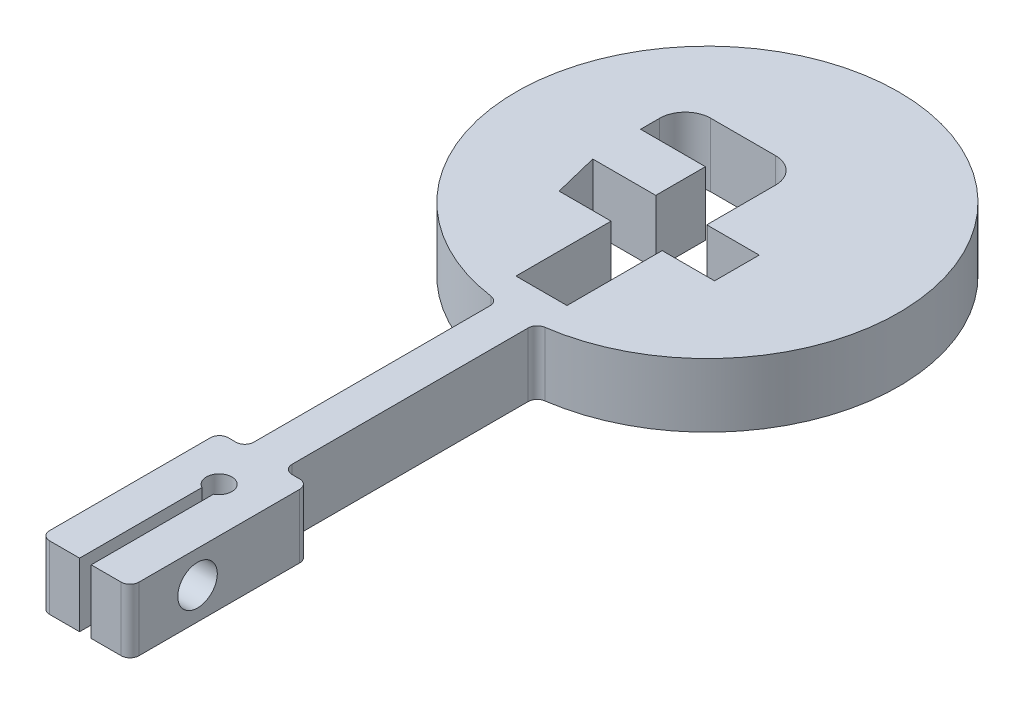
SolidWorks part; units mm, degrees
ref_plane "Front Plane" through (0, 0, 0) normal (0, 0, 1) x (1, 0, 0)
ref_plane "Top Plane" through (0, 0, 0) normal (0, 1, 0) x (1, 0, 0)
ref_plane "Right Plane" through (0, 0, 0) normal (1, 0, 0) x (0, 0, -1)
sketch "Sketch3" plane through (0, 0, 0) normal (0, 1, 0) x (1, 0, 0)
  line L0 (0.4546, -7) -> (0.4546, 2.8262)
  line L5 (-3.5, -7) -> (3.5, -7)
  line L6 (-3.5, -7) -> (-3.5, 7)
  line L7 (-3.5, 7) -> (3.5, 7)
  line L8 (3.5, -7) -> (3.5, 7)
  line L9 (-3.5, -7) -> (3.5, 7) construction
  line L10 (-3.5, 7) -> (3.5, -7) construction
  line L11 (0, -7) -> (-0.4546, -7)
  line L13 (0.4546, 2.8262) -> (-0.4546, 2.8262)
  line L14 (-0.4546, -7) -> (-0.4546, 2.8262)
  line L16 (-1.5, 7) -> (1.5, 7)
  line L17 (-1.5, 7) -> (-1.5, 27)
  line L19 (1.5, 7) -> (1.5, 27)
  line L20 (-1.5, 7) -> (1.5, 27) construction
  line L21 (-1.5, 27) -> (1.5, 7) construction
  line L24 (-1.5, 47.6013) -> (2.5, 47.6013)
  line L34 (0, 41.7579) -> (0, 56.7579) construction
  line L35 (-7.5824, 47.6013) -> (-7.5824, 44.1013)
  line L36 (1.5, 47.6013) -> (-7.5824, 47.6013)
  line L37 (1.5, 44.1013) -> (-7.5824, 44.1013)
  line L38 (-7.4355, 40.2089) -> (-6.5733, 36.7089)
  line L39 (5.6098, 40.2089) -> (-7.4355, 40.2089)
  line L40 (5.6098, 40.2089) -> (5.6098, 36.7089)
  line L41 (5.6098, 36.7089) -> (-7.4355, 36.7089)
  line L42 (-2.5, 27) -> (-2.5, 47.6013)
  line L43 (1.5, 27) -> (1.5, 47.6013)
  line L44 (1.5, 29.2512) -> (-2.5, 29.2512)
  circle A0 centre (0, 3.4821) radius 1
  circle A1 centre (0, 41.7579) radius 15
  point P0 (0, 0)
  point P10 (0, 17)
  dimension "D3" = 2
  dimension "D6" = 30
  dimension "D1" = 14
  dimension "D2" = 7
  dimension "D4" = 20
  dimension "D5" = 3
  dimension "D9" = 4
  dimension "D10" = 20.6013
extrude "Boss-Extrude2" add sketch "Sketch3" along normal blind 5
sketch "Sketch5" plane through (-3.5, 0, 0) normal (-1, 0, 0) x (0, 0, 1)
  line L0 (7, 5) -> (-7, 5) construction
  circle A0 centre (1.7109, 2.5) radius 1.55
  dimension "D1" = 3.1
  dimension "D2" = 2.5
extrude "Cut-Extrude1" cut sketch "Sketch5" against normal through all
fillet "Fillet6" radius 0.7 1 edges at (1.5, 2.5, -7)
fillet "Fillet7" radius 0.7 1 edges at (3.5, 2.5, -7)
fillet "Fillet8" radius 0.7 1 edges at (-1.5, 2.5, -7)
fillet "Fillet9" radius 0.7 1 edges at (-3.5, 2.5, -7)
fillet "Fillet10" radius 0.7 1 edges at (3.5, 2.5, 7)
fillet "Fillet11" radius 0.7 1 edges at (-3.5, 2.5, 7)
fillet "Fillet12" radius 0.7 1 edges at (1.5, 2.5, -26.8331)
fillet "Fillet13" radius 0.7 1 edges at (-1.5, 2.5, -26.8331)
fillet "Fillet14" radius 2 1 edges at (1.5, 2.5, -47.6013)
fillet "Fillet15" radius 2 1 edges at (-7.5824, 2.5, -47.6013)
